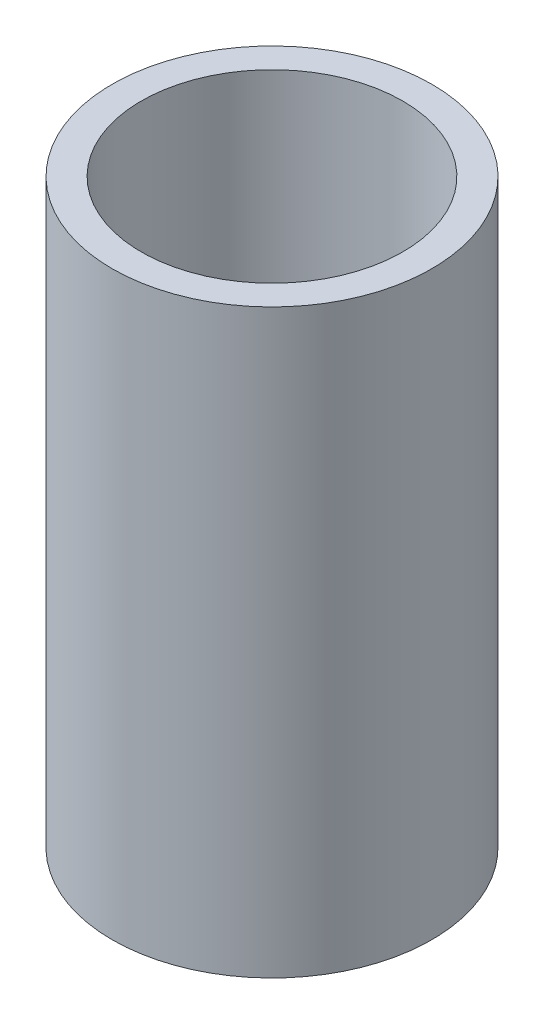
SolidWorks part; units mm, degrees
ref_plane "Спереди" through (0, 0, 0) normal (0, 0, 1) x (1, 0, 0)
ref_plane "Сверху" through (0, 0, 0) normal (0, 1, 0) x (1, 0, 0)
ref_plane "Справа" through (0, 0, 0) normal (1, 0, 0) x (0, 0, -1)
sketch "Эскиз1" plane through (0, 0, 0) normal (0, 0, 1) x (1, 0, 0)
  line L0 (0, -110.6031) -> (0, 130.0787) construction
  line L1 (45, 100) -> (55, 100)
  line L2 (45, 100) -> (45, -100)
  line L3 (45, -100) -> (55, -100)
  line L4 (55, 100) -> (55, -100)
  point P4 (45, 0)
  dimension "D1" = 10
  dimension "D2" = 200
  dimension "D3" = 45
revolve "Повернуть1" add sketch "Эскиз1" angle 360 about L0
ref_plane "Плоскость1" through (0, 0, 55) normal (0, 0, 1) x (1, 0, 0)
sketch "Эскиз2" plane through (0, 0, 55) normal (0, 0, 1) x (1, 0, 0)
  spline S0 degree 3 poles (-54.6404, -30.9953) (-37.7126, 28.6116) (8.4641, 64.6749) (54.8948, -29.3483) (-54.6404, -30.9953) (-37.7126, 28.6116) (8.4641, 64.6749) knots -0.813776 -0.511938 -0.19742 0 0.186224 0.488062 0.80258 1 1.186224 1.488062 1.80258 only from (-33.0608, 26.2387) to (-33.0608, 26.2387)
